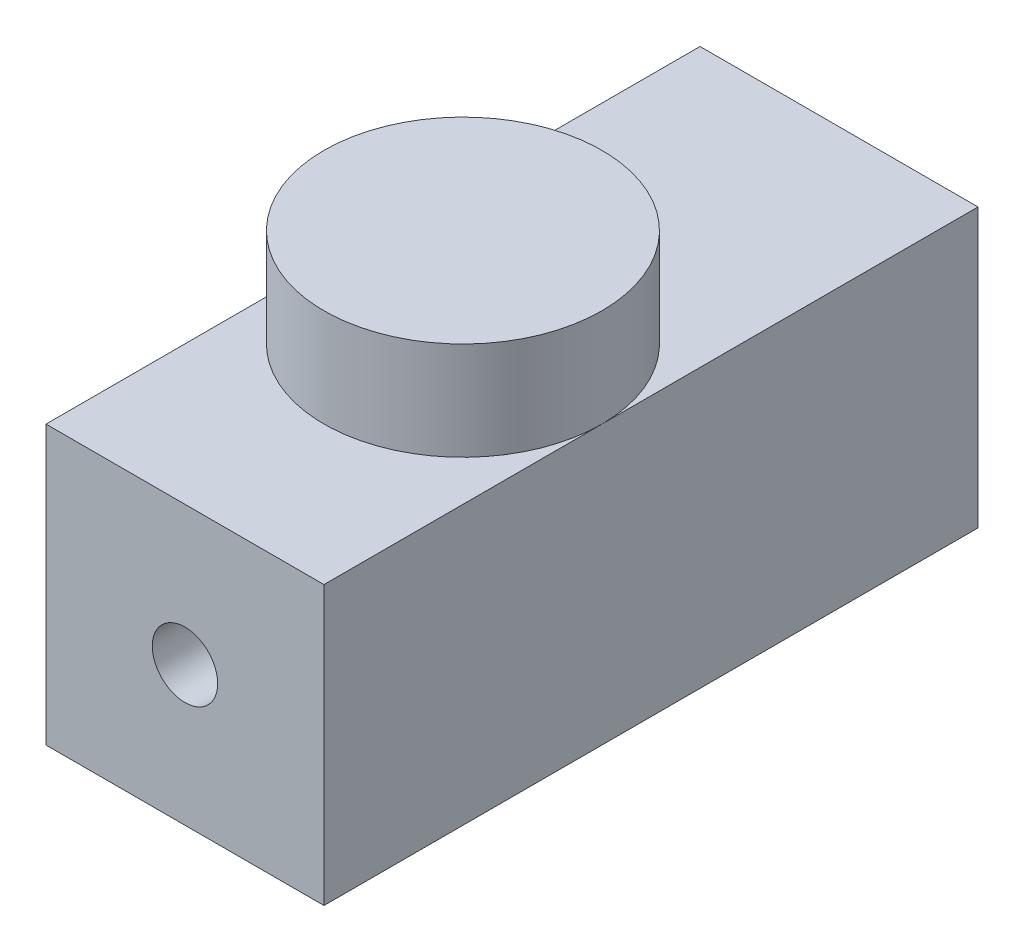
SolidWorks part; units mm, degrees
ref_plane "Спереди" through (0, 0, 0) normal (0, 0, 1) x (1, 0, 0)
ref_plane "Сверху" through (0, 0, 0) normal (0, 1, 0) x (1, 0, 0)
ref_plane "Справа" through (0, 0, 0) normal (1, 0, 0) x (0, 0, -1)
other "Configuration Table"
sketch "Эскиз1" plane through (0, 0, 0) normal (0, 0, 1) x (1, 0, 0)
  line L1 (8.5, -8.5) -> (-8.5, -8.5)
  line L2 (8.5, -8.5) -> (8.5, 8.5)
  line L3 (8.5, 8.5) -> (-8.5, 8.5)
  line L4 (-8.5, -8.5) -> (-8.5, 8.5)
  line L5 (8.5, -8.5) -> (-8.5, 8.5) construction
  line L6 (8.5, 8.5) -> (-8.5, -8.5) construction
  circle A0 centre (0, 0) radius 3.5
  dimension "D1" = 7
  dimension "D2" = 17
  dimension "D3" = 17
extrude "Бобышка-Вытянуть1" add sketch "Эскиз1" along normal blind 21
sketch "Эскиз2" plane through (0, 0, 21) normal (0, 0, 1) x (1, 0, 0)
  circle A0 centre (0, 0) radius 2
  dimension "D1" = 4
sketch "Эскиз4" plane through (0, 0, 0) normal (0, 0, -1) x (-1, 0, 0)
  line L2 (8.5, -8.5) -> (-8.5, -8.5)
  line L3 (8.5, -8.5) -> (8.5, 8.5)
  line L4 (8.5, 8.5) -> (-8.5, 8.5)
  line L5 (-8.5, -8.5) -> (-8.5, 8.5)
  line L6 (8.5, -8.5) -> (-8.5, 8.5) construction
  line L7 (8.5, 8.5) -> (-8.5, -8.5) construction
  point P2 (0, 0)
extrude "Бобышка-Вытянуть2" add sketch "Эскиз4" along normal blind 19
sketch "Эскиз5" plane through (0, 0, -19) normal (0, 0, -1) x (-1, 0, 0)
  line L8 (-8.5, 8.5) -> (-8.5, -8.5)
  line L9 (-8.5, -8.5) -> (8.5, -8.5)
  line L10 (8.5, -8.5) -> (8.5, 8.5)
  line L11 (8.5, 8.5) -> (-8.5, 8.5)
  line L12 (-8.5, 8.5) -> (-8.5, -8.5)
  line L13 (-8.5, -8.5) -> (8.5, -8.5)
  line L14 (8.5, -8.5) -> (8.5, 8.5)
  line L15 (8.5, 8.5) -> (-8.5, 8.5)
  circle A0 centre (0, 0) radius 3.5 construction
  circle A1 centre (0, 0) radius 3.5
  circle A2 centre (0, 0) radius 3
  dimension "D2" = 6
  dimension "D1" = 0
extrude "Вырез-Вытянуть2" cut sketch "Эскиз5" against normal blind 21 contours A2
sketch "Эскиз7" plane through (0, 8.5, 0) normal (0, 1, 0) x (1, 0, 0)
  line L0 (-8.5, -21) -> (-8.5, 19) construction
  line L1 (-8.5, 0) -> (8.5, 0)
  line L2 (-8.5, 0) -> (-8.5, -2.3644)
  line L3 (-8.5, -2.3644) -> (8.5, -2.3644)
  line L4 (8.5, 0) -> (8.5, -2.3644)
  line L5 (8.5, -21) -> (8.5, 19) construction
extrude "Бобышка-Вытянуть3" add sketch "Эскиз7" against normal blind 15
sketch "Эскиз9" plane through (0, 8.5, 0) normal (0, 1, 0) x (1, 0, 0)
  line L0 (-7.0501, -4) -> (-4.7424, -4)
  line L1 (4.7424, -4) -> (7.0501, -4)
  circle A0 centre (0, -4) radius 3
  circle A1 centre (0, -4) radius 4.7424
  circle A2 centre (0, -4) radius 7.0501
  dimension "D1" = 6
  dimension "D2" = 4
sketch "Эскиз10" plane through (0, 8.5, 0) normal (0, 1, 0) x (1, 0, 0)
  line L0 (-7.0501, -4) -> (-4.7424, -4)
  line L1 (4.7424, -4) -> (7.0501, -4)
  arc A0 (-4.7424, -4) -> (4.7424, -4) centre (0, -4) cw
  arc A1 (7.0501, -4) -> (-7.0501, -4) centre (0, -4) ccw
extrude "Вырез-Вытянуть5" cut sketch "Эскиз10" against normal blind 10
extrude "Вырез-Вытянуть6" cut sketch "Эскиз9" against normal blind 10 contours A0
sketch "Эскиз12" plane through (0, 8.5, 0) normal (0, 1, 0) x (1, 0, 0)
  line L1 (-2.5149, -2.3644) -> (2.5149, -2.3644)
  line L2 (-2.5149, -2.3644) -> (2.5149, -2.3644)
  arc A0 (7.0501, -4) -> (-7.0501, -4) centre (0, -4) ccw construction
  arc A1 (2.5149, -2.3644) -> (-2.5149, -2.3644) centre (0, -4) ccw
  arc A2 (2.5149, -2.3644) -> (-2.5149, -2.3644) centre (0, -4) ccw
  arc A3 (7.0501, -4) -> (-7.0501, -4) centre (0, -4) ccw
  circle A4 centre (0, -4) radius 7.0501
  circle A5 centre (0, -4) radius 8.5
  arc M7 (-7.0501, -4) -> (7.0501, -4) centre (0, -4) cw
  dimension "D1" = 0
extrude "Бобышка-Вытянуть4" add sketch "Эскиз12" along normal blind 5 contours A5 A4 M7
sketch "Эскиз13" plane through (0, 13.5, 0) normal (0, 1, 0) x (1, 0, 0)
  circle A1 centre (0, -4) radius 8.5
  circle A2 centre (0, -4) radius 8.5
  dimension "D1" = 0
extrude "Бобышка-Вытянуть5" add sketch "Эскиз13" along normal blind 1
sketch "Эскиз15" plane through (0, 0, 21) normal (0, 0, 1) x (1, 0, 0)
  circle A0 centre (0, 0) radius 5.5126
  circle A1 centre (0, 0) radius 2
  dimension "D1" = 4
extrude "Бобышка-Вытянуть6" add sketch "Эскиз15" against normal blind 5
sketch "Эскиз16" plane through (0, 0, -19) normal (0, 0, -1) x (-1, 0, 0)
  circle A0 centre (0, 0) radius 2
  circle A1 centre (0, 0) radius 4.0745
  dimension "D1" = 4
extrude "Бобышка-Вытянуть7" add sketch "Эскиз16" against normal blind 7
